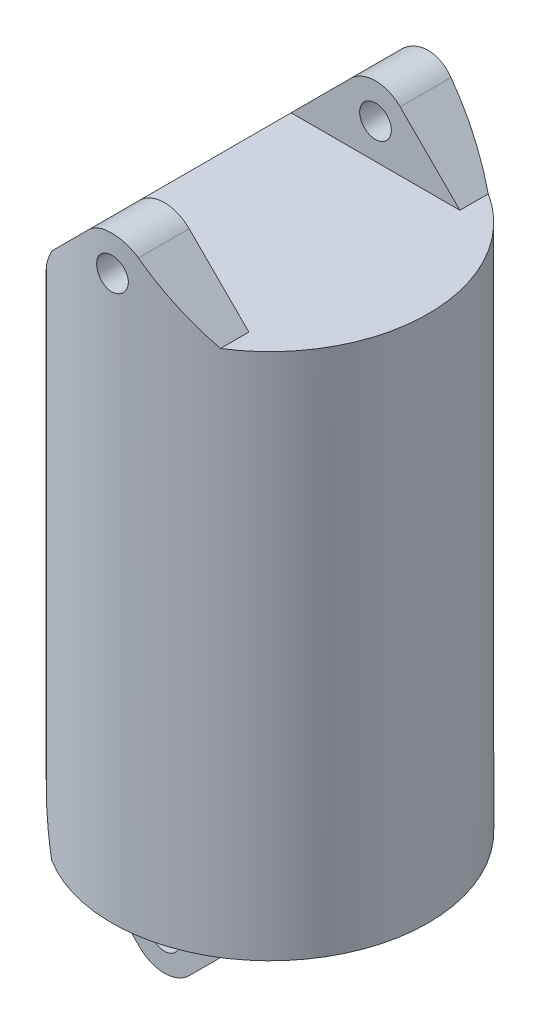
SolidWorks part; units mm, degrees
ref_plane "Alzado" through (0, 0, 0) normal (0, 0, 1) x (1, 0, 0)
ref_plane "Planta" through (0, 0, 0) normal (0, 1, 0) x (1, 0, 0)
ref_plane "Vista lateral" through (0, 0, 0) normal (1, 0, 0) x (0, 0, -1)
sketch "Croquis1" plane through (0, 0, 0) normal (0, 1, 0) x (1, 0, 0)
  circle A0 centre (0, 0) radius 15
  dimension "D1" = 30
extrude "Saliente-Extruir1" add sketch "Croquis1" along normal blind 50
sketch "Croquis2" plane through (0, 0, 0) normal (0, 0, 1) x (1, 0, 0)
  line L0 (-8, 0) -> (-2.3431, -5.6569)
  line L1 (-15, 0) -> (15, 0) construction
  line L2 (0, -16.5) -> (0, 16.5) construction
  line L3 (8, 0) -> (2.3431, -5.6569)
  line L4 (-8, 0) -> (8, 0)
  arc A0 (-2.3431, -5.6569) -> (2.3431, -5.6569) centre (0, -3.3137) ccw
  dimension "D1" = 8
  dimension "D2" = 8
  dimension "D3" = 45
extrude "Saliente-Extruir2" add sketch "Croquis2" along normal blind 5 from offset 5
sketch "Croquis3" plane through (0, 0, 10) normal (0, 0, 1) x (1, 0, 0)
  circle A0 centre (0, -3.3137) radius 1.5
  dimension "D1" = 3
extrude "Cortar-Extruir1" cut sketch "Croquis3" against normal blind 5
mirror "Simetría1" about plane through (0, 0, 0) normal (0, 0, 1) of "Saliente-Extruir2", "Cortar-Extruir1"
sketch "Croquis4" plane through (0, 0, 0) normal (0, 0, 1) x (1, 0, 0)
  line L0 (-8, 0) -> (-15, 0)
  line L2 (-15, 0) -> (15, 0) construction
  line L3 (-15, 0) -> (-15, 10)
  line L4 (-15, 50) -> (-15, 0) construction
  line L5 (-15, 10) -> (-8, 0)
  dimension "D1" = 7
  dimension "D2" = 10
extrude "Cortar-Extruir2" cut sketch "Croquis4" against normal mid plane 50
ref_plane "Plano1" through (0, 25, 0) normal (0, 1, 0) x (1, 0, 0)
mirror "Simetría2" about plane through (0, 25, 0) normal (0, 1, 0) of "Cortar-Extruir2"
sketch "Croquis5" plane through (0, 0, 0) normal (0, 0, 1) x (1, 0, 0)
  line L0 (-8, 50) -> (-2.3431, 55.6569)
  line L1 (0, 0) -> (0, 50) construction
  line L2 (15, 50) -> (-8, 50) construction
  line L3 (8, 50) -> (2.3431, 55.6569)
  line L4 (-8, 50) -> (8, 50)
  arc A0 (-2.3431, 55.6569) -> (2.3431, 55.6569) centre (0, 53.3137) cw
  circle A1 centre (0, 53.3137) radius 1.5
  dimension "D3" = 3
  dimension "D1" = 8
  dimension "D2" = 45
extrude "Saliente-Extruir3" add sketch "Croquis5" along normal blind 5 from offset 10
mirror "Simetría3" about plane through (0, 0, 0) normal (0, 0, 1) of "Saliente-Extruir3"
sketch "Croquis6" plane through (0, 50, 0) normal (0, 1, 0) x (1, 0, 0)
  circle A0 centre (0, 0) radius 15
  circle A1 centre (0, 0) radius 22.2804
extrude "Cortar-Extruir3" cut sketch "Croquis6" along normal blind 20
